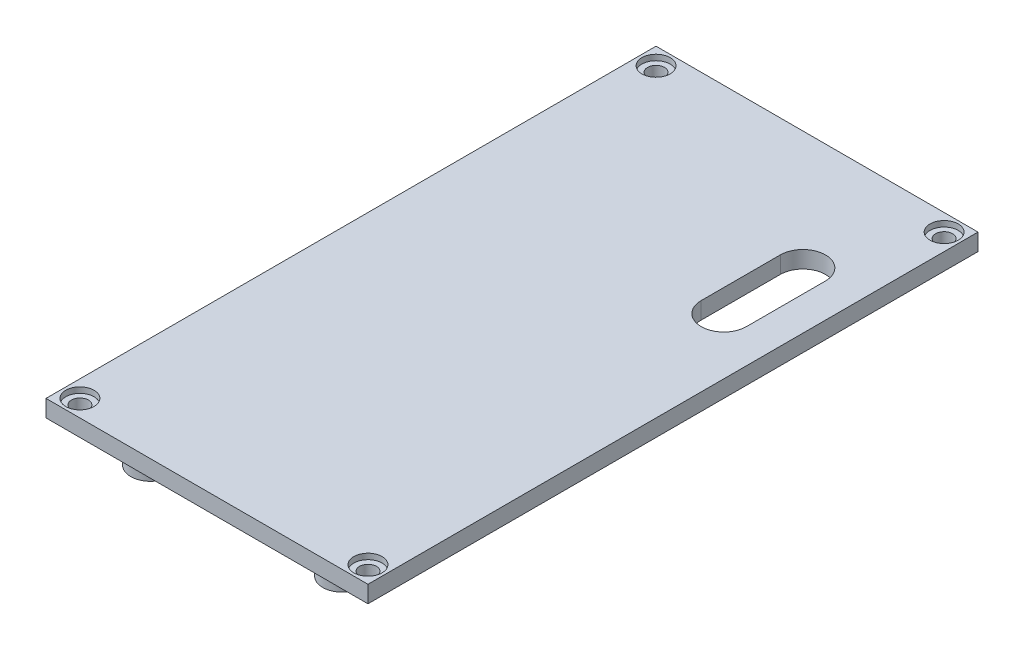
SolidWorks part; units mm, degrees
ref_plane "Alzado" through (0, 0, 0) normal (0, 0, 1) x (1, 0, 0)
ref_plane "Planta" through (0, 0, 0) normal (0, 1, 0) x (1, 0, 0)
ref_plane "Vista lateral" through (0, 0, 0) normal (1, 0, 0) x (0, 0, -1)
sketch "Croquis1" plane through (0, 0, 0) normal (0, 1, 0) x (1, 0, 0)
  line L1 (-28.5, 54) -> (28.5, 54)
  line L2 (-28.5, 54) -> (-28.5, -54)
  line L3 (-28.5, -54) -> (28.5, -54)
  line L4 (28.5, 54) -> (28.5, -54)
  point P4 (0, 54)
  point P6 (-28.5, 0)
  dimension "D1" = 108
  dimension "D2" = 57
extrude "Saliente-Extruir1" add sketch "Croquis1" along normal blind 3
sketch "Croquis2" plane through (0, 3, 0) normal (0, 1, 0) x (1, 0, 0)
  line L0 (28.5, 54) -> (-28.5, 54) construction
  line L1 (-28.5, 54) -> (-28.5, -54) construction
  line L2 (28.5, -54) -> (28.5, 54) construction
  line L3 (-28.5, -54) -> (28.5, -54) construction
  circle A0 centre (-25.5, 51) radius 1.5
  circle A1 centre (25.5, 51) radius 1.5
  circle A2 centre (25.5, -51) radius 1.5
  circle A3 centre (-25.5, -51) radius 1.5
  dimension "D1" = 3
  dimension "D3" = 3
  dimension "D4" = 3
  dimension "D5" = 3
  dimension "D8" = 3
  dimension "D9" = 3
  dimension "D10" = 3
  dimension "D12" = 3
  dimension "D2" = 3
  dimension "D6" = 3
  dimension "D7" = 3
  dimension "D11" = 3
extrude "Cortar-Extruir1" cut sketch "Croquis2" against normal blind 3
sketch "Croquis3" plane through (0, 3, 0) normal (0, 1, 0) x (1, 0, 0)
  circle A0 centre (-25.5, 51) radius 2.5
  circle A1 centre (25.5, 51) radius 2.5
  circle A2 centre (-25.5, 51) radius 1.5 construction
  circle A3 centre (25.5, 51) radius 1.5 construction
  circle A4 centre (25.5, -51) radius 2.5
  circle A5 centre (25.5, -51) radius 1.5 construction
  circle A6 centre (-25.5, -51) radius 2.5
  circle A7 centre (-25.5, -51) radius 1.5 construction
  dimension "D1" = 5
  dimension "D2" = 5
  dimension "D3" = 5
  dimension "D4" = 5
extrude "Cortar-Extruir2" cut sketch "Croquis3" against normal blind 1
sketch "Croquis5" plane through (0, 0, 0) normal (0, -1, 0) x (1, 0, 0)
  line L1 (-19, 49.5) -> (19, 49.5) construction
  line L2 (-24, 44.5) -> (-24, -44.5) construction
  line L3 (-19, -49.5) -> (19, -49.5) construction
  line L4 (24, 44.5) -> (24, -44.5) construction
  arc A0 (-19, 49.5) -> (-24, 44.5) centre (-19, 44.5) ccw construction
  arc A1 (24, 44.5) -> (19, 49.5) centre (19, 44.5) ccw construction
  arc A2 (-24, -44.5) -> (-19, -49.5) centre (-19, -44.5) ccw construction
  arc A3 (19, -49.5) -> (24, -44.5) centre (19, -44.5) ccw construction
  point P4 (0, -49.5)
  point P6 (24, 0)
  dimension "D3" = 10
  dimension "D4" = 10
  dimension "D5" = 10
  dimension "D6" = 10
  dimension "D1" = 99
sketch "Croquis7" plane through (0, 0, 0) normal (0, -1, 0) x (1, 0, 0)
  line L0 (-24, 44.5) -> (-24, -44.5) construction
  line L1 (-19, 49.5) -> (19, 49.5) construction
  line L2 (24, 44.5) -> (24, -44.5) construction
  line L3 (-19, -49.5) -> (19, -49.5) construction
  circle A0 centre (-17, 47) radius 1.5
  circle A1 centre (17, 47) radius 1.5
  circle A2 centre (-17, -47) radius 1.5
  circle A3 centre (17, -47) radius 1.5
  circle A4 centre (-17, 47) radius 3.5
  circle A5 centre (17, 47) radius 3.5
  circle A6 centre (17, -47) radius 3.5
  circle A7 centre (-17, -47) radius 3.5
  dimension "D1" = 3
  dimension "D4" = 3
  dimension "D5" = 2.5
  dimension "D6" = 7
  dimension "D7" = 3
  dimension "D8" = 7
  dimension "D9" = 2.5
  dimension "D10" = 3
  dimension "D11" = 2.5
  dimension "D12" = 7
  dimension "D13" = 7
  dimension "D14" = 7
  dimension "D15" = 7
  dimension "D16" = 7
  dimension "D2" = 7
  dimension "D3" = 2.5
extrude "Saliente-Extruir2" add sketch "Croquis7" along normal blind 5
sketch "Croquis9" plane through (0, 3, 0) normal (0, 1, 0) x (1, 0, 0)
  line L0 (28.5, -54) -> (28.5, 54) construction
  line L2 (14.5, 33) -> (14.5, 19)
  line L4 (22.5, 33) -> (22.5, 19)
  arc A0 (22.5, 33) -> (14.5, 33) centre (18.5, 33) ccw
  arc A1 (14.5, 19) -> (22.5, 19) centre (18.5, 19) ccw
  dimension "D1" = 8
  dimension "D2" = 14
  dimension "D3" = 6
extrude "Cortar-Extruir3" cut sketch "Croquis9" against normal blind 4
